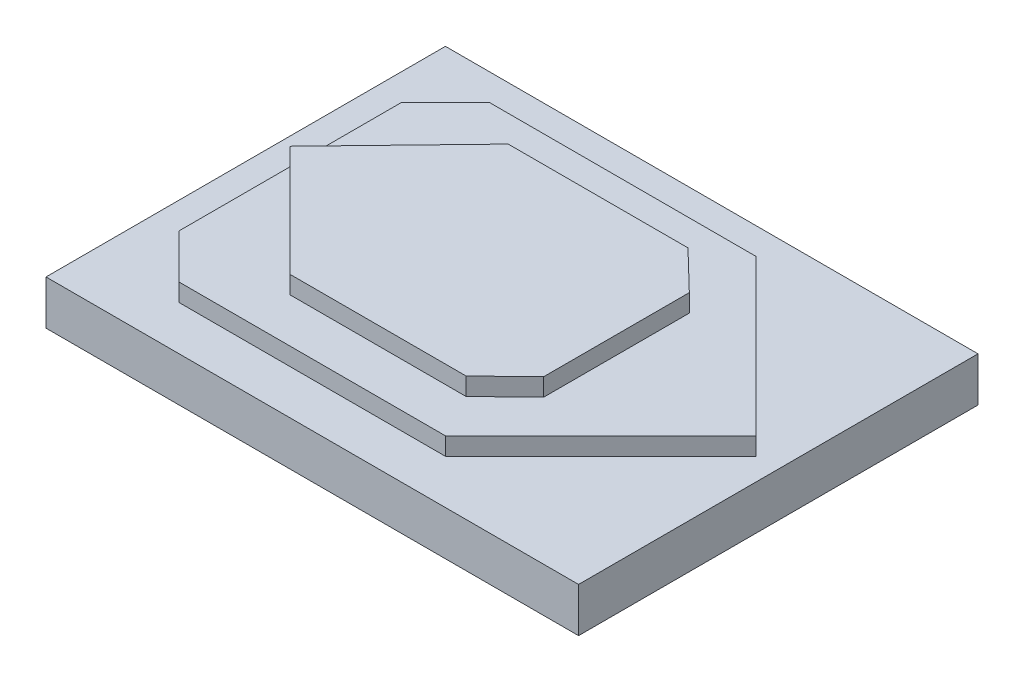
SolidWorks part; units mm, degrees
ref_plane "Front Plane" through (0, 0, 0) normal (0, 0, 1) x (1, 0, 0)
ref_plane "Top Plane" through (0, 0, 0) normal (0, 1, 0) x (1, 0, 0)
ref_plane "Right Plane" through (0, 0, 0) normal (1, 0, 0) x (0, 0, -1)
sketch "Sketch1" plane through (0, 0, 0) normal (0, 1, 0) x (1, 0, 0)
  line L1 (0, 0) -> (120, 0)
  line L2 (0, 0) -> (0, 90)
  line L3 (0, 90) -> (120, 90)
  line L4 (120, 0) -> (120, 90)
  line L5 (0, 0) -> (120, 90) construction
  line L6 (0, 90) -> (120, 0) construction
  point P5 (60, 45)
  dimension "D1" = 120
  dimension "D2" = 90
extrude "Boss-Extrude1" add sketch "Sketch1" along normal blind 10
sketch "Sketch2" plane through (0, 10, 0) normal (0, 1, 0) x (1, 0, 0)
  line L0 (10, 70) -> (20, 80)
  line L1 (20, 80) -> (80, 80)
  line L2 (80, 80) -> (115, 45)
  line L3 (115, 45) -> (80, 10)
  line L4 (80, 10) -> (20, 10)
  line L5 (20, 10) -> (10, 20)
  line L6 (10, 20) -> (10, 70)
  line L7 (0, 0) -> (120, 0) construction
  line L9 (0, 90) -> (0, 0) construction
  line L10 (120, 0) -> (120, 90) construction
  line L11 (120, 90) -> (0, 90) construction
  dimension "D1" = 20
  dimension "D2" = 10
  dimension "D3" = 10
  dimension "D4" = 45
  dimension "D5" = 5
  dimension "D6" = 360
  dimension "D7" = 10
  dimension "D8" = 80
extrude "Boss-Extrude2" add sketch "Sketch2" along normal blind 4
ref_plane "Plane1" through (0, 18, 0) normal (0, -1, 0) x (-1, 0, 0)
sketch "Sketch3" plane through (0, 18, 0) normal (0, -1, 0) x (-1, 0, 0)
  line L0 (-10, 45) -> (-34.1422, 70)
  line L1 (-10, 70) -> (-10, 20) construction
  line L2 (-34.1422, 70) -> (-74.652, 70)
  line L3 (-74.652, 70) -> (-83.5342, 61.4226)
  line L4 (-83.5342, 61.4226) -> (-83.5342, 43.1692)
  line L5 (-83.5342, 43.1692) -> (-83.5342, 28.5842)
  line L6 (-83.5342, 28.5842) -> (-74.645, 20)
  line L7 (-74.645, 20) -> (-35, 20)
  line L8 (-35, 20) -> (-10, 45)
  line L9 (-74.652, 70) -> (-84.0333, 70) construction
  line L10 (-74.645, 20) -> (-90.6445, 35.4506) construction
  line L11 (0, 90) -> (0, 0) construction
  line L13 (-120, 90) -> (0, 90) construction
  line L14 (0, 0) -> (-120, 0) construction
  dimension "D1" = 44
  dimension "D2" = 46
  dimension "D3" = 35
  dimension "D4" = 74.645
  dimension "D5" = 20
  dimension "D6" = 20
extrude "Boss-Extrude3" add sketch "Sketch3" along normal blind 4
